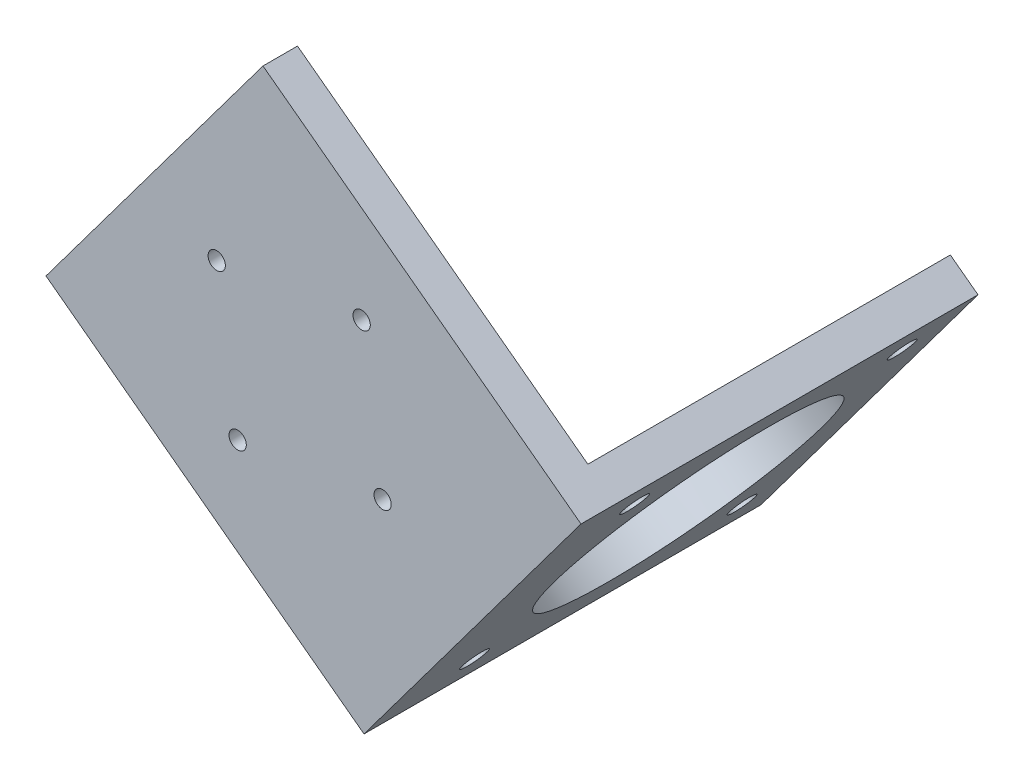
SolidWorks part; units mm, degrees
ref_plane "前视基准面" through (0, 0, 0) normal (0, 0, 1) x (1, 0, 0)
ref_plane "上视基准面" through (0, 0, 0) normal (0, 1, 0) x (1, 0, 0)
ref_plane "右视基准面" through (0, 0, 0) normal (1, 0, 0) x (0, 0, -1)
sketch "草图2" plane through (0, 0, -18) normal (0, 0, -1) x (-1, 0, 0)
  line L0 (0, 0) -> (7.1833, -9.6125) construction
  line L1 (0, 0) -> (-9.6125, -7.1833) construction
  line L2 (8.9202, -11.4355) -> (8.4395, -11.7947) construction
  line L8 (-4.251, -29.3927) -> (29.3927, -4.251)
  line L9 (-4.251, -29.3927) -> (-29.3927, 4.251)
  line L10 (29.3927, -4.251) -> (4.251, 29.3927)
  line L11 (-29.3927, 4.251) -> (4.251, 29.3927)
  line L12 (12.5708, -16.8218) -> (-12.5708, 16.8218) construction
  circle A0 centre (9.6125, 7.1833) radius 1 construction
  circle A1 centre (-7.1833, 9.6125) radius 1 construction
  circle A2 centre (-9.6125, -7.1833) radius 1 construction
  circle A3 centre (7.1833, -9.6125) radius 1 construction
  circle A4 centre (9.6125, 7.1833) radius 1
  circle A5 centre (-7.1833, 9.6125) radius 1
  circle A6 centre (-9.6125, -7.1833) radius 1
  circle A7 centre (7.1833, -9.6125) radius 1
  point P14 (16.8218, 12.5708)
  point P16 (-16.8218, -12.5708)
  dimension "D1" = 42
  dimension "D2" = 42
extrude "凸台-拉伸1" add sketch "草图2" along normal blind 4
sketch "草图5" plane through (16.8218, -12.5708, 0) normal (0.801, -0.5986, 0) x (0.5986, 0.801, 0)
  line L4 (21, -18) -> (-21, -18)
  line L5 (-21, -18) -> (-21, -22)
  line L6 (-21, -22) -> (21, -22)
  line L7 (21, -22) -> (21, -18)
  line L8 (21, -18) -> (-21, -18)
  line L9 (-21, -18) -> (-21, -22)
  line L10 (-21, -22) -> (21, -22)
  line L11 (21, -22) -> (21, -18)
  dimension "D1" = 0
extrude "凸台-拉伸2" add sketch "草图5" along normal blind 4
sketch "草图6" plane through (0, 0, -22) normal (0, 0, -1) x (-1, 0, 0)
  line L0 (-7.4552, -31.7871) -> (-32.5968, 1.8566)
  line L1 (-32.5968, 1.8566) -> (-29.3927, 4.251)
  line L2 (4.251, 29.3927) -> (-32.5968, 1.8566) construction
  line L3 (-29.3927, 4.251) -> (-4.251, -29.3927)
  line L4 (-7.4552, -31.7871) -> (29.3927, -4.251) construction
  line L5 (-4.251, -29.3927) -> (-7.4552, -31.7871)
  dimension "D1" = 4
extrude "凸台-拉伸3" add sketch "草图6" along normal blind 42 contours L5 L0 L1 L3
sketch "草图7" plane through (20.026, -14.9653, 0) normal (0.801, -0.5986, 0) x (-0.5986, -0.801, 0)
  line L0 (21, 18) -> (21, 64) construction
  line L1 (-21, 64) -> (21, 64)
  line L2 (-21, 64) -> (-21, 22)
  line L3 (-21, 22) -> (21, 22)
  line L4 (21, 64) -> (21, 22)
  line L5 (-21, 43) -> (21, 43) construction
  line L6 (0, 22) -> (0, 64) construction
  circle A0 centre (0, 43) radius 15.5
  dimension "D2" = 31
  dimension "D1" = 42
extrude "切除-拉伸1" cut sketch "草图7" against normal up to next contours A0
sketch "草图9" plane through (20.026, -14.9653, 0) normal (0.801, -0.5986, 0) x (-0.5986, -0.801, 0)
  line L0 (21, 18) -> (21, 64) construction
  line L1 (-21, 64) -> (21, 64)
  line L2 (-21, 64) -> (-21, 22)
  line L3 (-21, 22) -> (21, 22)
  line L4 (21, 64) -> (21, 22)
  line L5 (-21, 43) -> (21, 43) construction
  line L6 (0, 22) -> (0, 64) construction
  circle A0 centre (-15.5, 58.5) radius 1.5
  circle A1 centre (-15.5, 27.5) radius 1.5
  circle A2 centre (15.5, 58.5) radius 1.5
  circle A3 centre (15.5, 27.5) radius 1.5
  dimension "D2" = 3
  dimension "D1" = 42
  dimension "D3" = 31
  dimension "D4" = 31
extrude "切除-拉伸2" cut sketch "草图9" against normal up to next contours A3 | A1 | A0 | A2
